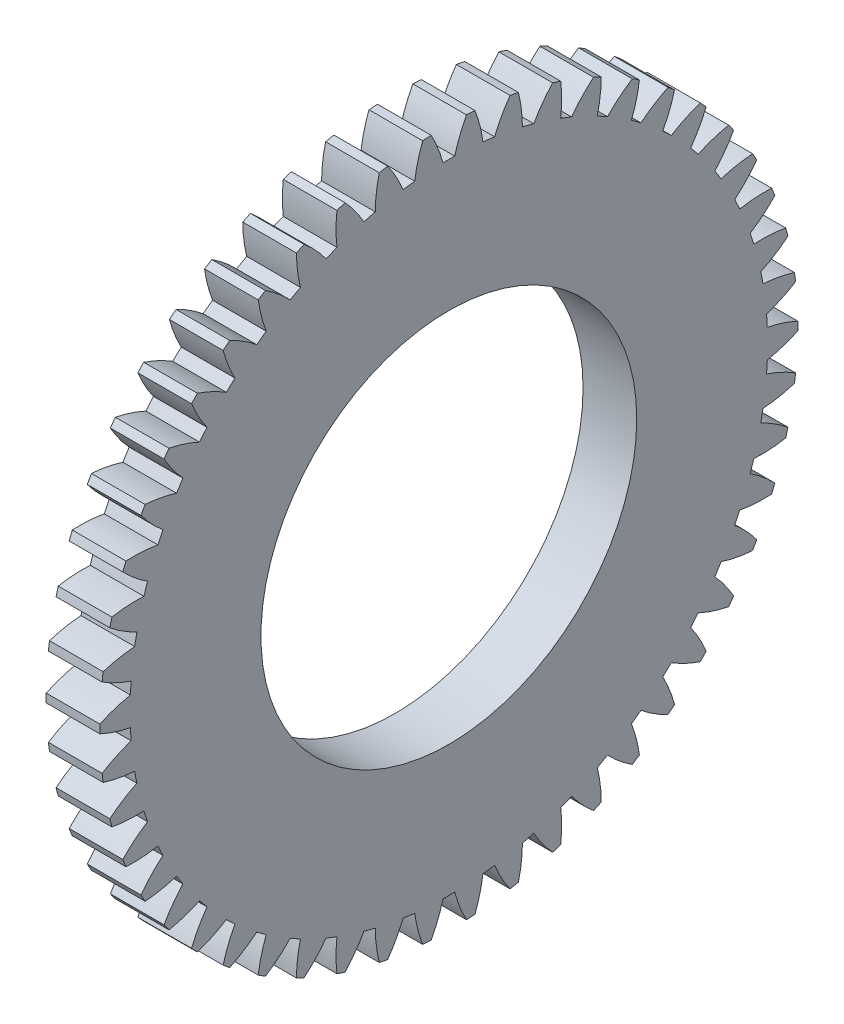
SolidWorks part; units mm, degrees
ref_plane "Front Plane" through (0, 0, 0) normal (0, 0, 1) x (1, 0, 0)
ref_plane "Top Plane" through (0, 0, 0) normal (0, 1, 0) x (1, 0, 0)
ref_plane "Right Plane" through (0, 0, 0) normal (1, 0, 0) x (0, 0, -1)
ref_plane "Plane1" through (-24.3289, 0, 0) normal (1, 0, 0) x (0, 0, -1)
sketch "Sketch1" plane through (-24.3289, 0, 0) normal (1, 0, 0) x (0, 0, -1)
  arc A0 (-24.5536, 1.2423) -> (-24.5261, 0.8057) centre (-12.6913, 1.7694) ccw
  arc A1 (-24.5261, 0.8057) -> (-25.6077, 0.2975) centre (-22.9558, -3.9413) ccw
  arc A2 (-25.6077, 0.2975) -> (-25.5679, -0.0171) centre (-12.6913, 1.7694) ccw
  arc A3 (-25.5679, -0.0171) -> (-24.3939, -0.2403) centre (-24.0535, 4.7481) ccw
  arc A4 (-24.3939, -0.2403) -> (-24.312, -0.67) centre (-12.6913, 1.7694) ccw
  arc A5 (-24.312, -0.67) -> (-25.3213, -1.3097) centre (-22.1591, -5.1827) ccw
  arc A6 (-25.3213, -1.3097) -> (-25.2425, -1.6168) centre (-12.6913, 1.7694) ccw
  arc A7 (-25.2425, -1.6168) -> (-24.0498, -1.6912) centre (-24.3372, 3.3005) ccw
  arc A8 (-24.0498, -1.6912) -> (-23.9146, -2.1072) centre (-12.6913, 1.7694) ccw
  arc A9 (-23.9146, -2.1072) -> (-24.8358, -2.8684) centre (-21.2131, -6.3145) ccw
  arc A10 (-24.8358, -2.8684) -> (-24.7191, -3.1632) centre (-12.6913, 1.7694) ccw
  arc A11 (-24.7191, -3.1632) -> (-23.5265, -3.0875) centre (-24.4373, 1.8288) ccw
  arc A12 (-23.5265, -3.0875) -> (-23.3402, -3.4833) centre (-12.6913, 1.7694) ccw
  arc A13 (-23.3402, -3.4833) -> (-24.1588, -4.354) centre (-20.1327, -7.3189) ccw
  arc A14 (-24.1588, -4.354) -> (-24.006, -4.6318) centre (-12.6913, 1.7694) ccw
  arc A15 (-24.006, -4.6318) -> (-22.8323, -4.4072) centre (-24.3521, 0.3562) ccw
  arc A16 (-22.8323, -4.4072) -> (-22.5979, -4.7765) centre (-12.6913, 1.7694) ccw
  arc A17 (-22.5979, -4.7765) -> (-23.3009, -5.7429) centre (-18.935, -8.1799) ccw
  arc A18 (-23.3009, -5.7429) -> (-23.1145, -5.9995) centre (-12.6913, 1.7694) ccw
  arc A19 (-23.1145, -5.9995) -> (-21.9782, -5.6295) centre (-24.083, -1.0942) ccw
  arc A20 (-21.9782, -5.6295) -> (-21.6994, -5.9666) centre (-12.6913, 1.7694) ccw
  arc A21 (-21.6994, -5.9666) -> (-22.2757, -7.0134) centre (-17.6387, -8.884) ccw
  arc A22 (-22.2757, -7.0134) -> (-22.0586, -7.2446) centre (-12.6913, 1.7694) ccw
  arc A23 (-22.0586, -7.2446) -> (-20.9776, -6.7352) centre (-23.6343, -2.4993) ccw
  arc A24 (-20.9776, -6.7352) -> (-20.6588, -7.0346) centre (-12.6913, 1.7694) ccw
  arc A25 (-20.6588, -7.0346) -> (-21.0993, -8.1454) centre (-16.2645, -9.42) ccw
  arc A26 (-21.0993, -8.1454) -> (-20.855, -8.3475) centre (-12.6913, 1.7694) ccw
  arc A27 (-20.855, -8.3475) -> (-19.8464, -7.7067) centre (-23.013, -3.8372) ccw
  arc A28 (-19.8464, -7.7067) -> (-19.4925, -7.9637) centre (-12.6913, 1.7694) ccw
  arc A29 (-19.4925, -7.9637) -> (-19.7904, -9.1211) centre (-14.8339, -9.7796) ccw
  arc A30 (-19.7904, -9.1211) -> (-19.5226, -9.291) centre (-12.6913, 1.7694) ccw
  arc A31 (-19.5226, -9.291) -> (-18.6023, -8.5287) centre (-22.2289, -5.0866) ccw
  arc A32 (-18.6023, -8.5287) -> (-18.219, -8.7394) centre (-12.6913, 1.7694) ccw
  arc A33 (-18.219, -8.7394) -> (-18.3694, -9.9249) centre (-13.3695, -9.9571) ccw
  arc A34 (-18.3694, -9.9249) -> (-18.0825, -10.0599) centre (-12.6913, 1.7694) ccw
  arc A35 (-18.0825, -10.0599) -> (-17.265, -9.1883) centre (-21.2944, -6.228) ccw
  arc A36 (-17.265, -9.1883) -> (-16.8583, -9.3494) centre (-12.6913, 1.7694) ccw
  arc A37 (-16.8583, -9.3494) -> (-16.859, -10.5444) centre (-11.8945, -9.9497) ccw
  arc A38 (-16.859, -10.5444) -> (-16.5574, -10.6424) centre (-12.6913, 1.7694) ccw
  arc A39 (-16.5574, -10.6424) -> (-15.8555, -9.6752) centre (-20.2242, -7.2432) ccw
  arc A40 (-15.8555, -9.6752) -> (-15.4319, -9.784) centre (-12.6913, 1.7694) ccw
  arc A41 (-15.4319, -9.784) -> (-15.2828, -10.9696) centre (-10.4319, -9.7574) ccw
  arc A42 (-15.2828, -10.9696) -> (-14.9713, -11.0291) centre (-12.6913, 1.7694) ccw
  arc A43 (-14.9713, -11.0291) -> (-14.3962, -9.9815) centre (-19.0352, -8.1162) ccw
  arc A44 (-14.3962, -9.9815) -> (-13.9622, -10.0363) centre (-12.6913, 1.7694) ccw
  arc A45 (-13.9622, -10.0363) -> (-13.6657, -11.194) centre (-9.0051, -9.3833) ccw
  arc A46 (-13.6657, -11.194) -> (-13.3493, -11.2139) centre (-12.6913, 1.7694) ccw
  arc A47 (-13.3493, -11.2139) -> (-12.91, -10.1025) centre (-17.7462, -8.8334) ccw
  arc A48 (-12.91, -10.1025) -> (-12.4726, -10.1025) centre (-12.6913, 1.7694) ccw
  arc A49 (-12.4726, -10.1025) -> (-12.0333, -11.2139) centre (-7.6363, -8.8334) ccw
  arc A50 (-12.0333, -11.2139) -> (-11.7168, -11.194) centre (-12.6913, 1.7694) ccw
  arc A51 (-11.7168, -11.194) -> (-11.4203, -10.0363) centre (-16.3775, -9.3833) ccw
  arc A52 (-11.4203, -10.0363) -> (-10.9863, -9.9815) centre (-12.6913, 1.7694) ccw
  arc A53 (-10.9863, -9.9815) -> (-10.4112, -11.0291) centre (-6.3473, -8.1162) ccw
  arc A54 (-10.4112, -11.0291) -> (-10.0998, -10.9696) centre (-12.6913, 1.7694) ccw
  arc A55 (-10.0998, -10.9696) -> (-9.9507, -9.784) centre (-14.9506, -9.7574) ccw
  arc A56 (-9.9507, -9.784) -> (-9.527, -9.6752) centre (-12.6913, 1.7694) ccw
  arc A57 (-9.527, -9.6752) -> (-8.8251, -10.6424) centre (-5.1583, -7.2432) ccw
  arc A58 (-8.8251, -10.6424) -> (-8.5236, -10.5444) centre (-12.6913, 1.7694) ccw
  arc A59 (-8.5236, -10.5444) -> (-8.5242, -9.3494) centre (-13.4881, -9.9497) ccw
  arc A60 (-8.5242, -9.3494) -> (-8.1176, -9.1883) centre (-12.6913, 1.7694) ccw
  arc A61 (-8.1176, -9.1883) -> (-7.3, -10.0599) centre (-4.0881, -6.228) ccw
  arc A62 (-7.3, -10.0599) -> (-7.0131, -9.9249) centre (-12.6913, 1.7694) ccw
  arc A63 (-7.0131, -9.9249) -> (-7.1635, -8.7394) centre (-12.013, -9.9571) ccw
  arc A64 (-7.1635, -8.7394) -> (-6.7802, -8.5287) centre (-12.6913, 1.7694) ccw
  arc A65 (-6.7802, -8.5287) -> (-5.8599, -9.291) centre (-3.1536, -5.0866) ccw
  arc A66 (-5.8599, -9.291) -> (-5.5922, -9.1211) centre (-12.6913, 1.7694) ccw
  arc A67 (-5.5922, -9.1211) -> (-5.89, -7.9637) centre (-10.5486, -9.7796) ccw
  arc A68 (-5.89, -7.9637) -> (-5.5362, -7.7067) centre (-12.6913, 1.7694) ccw
  arc A69 (-5.5362, -7.7067) -> (-4.5275, -8.3475) centre (-2.3696, -3.8372) ccw
  arc A70 (-4.5275, -8.3475) -> (-4.2832, -8.1454) centre (-12.6913, 1.7694) ccw
  arc A71 (-4.2832, -8.1454) -> (-4.7238, -7.0346) centre (-9.118, -9.42) ccw
  arc A72 (-4.7238, -7.0346) -> (-4.4049, -6.7352) centre (-12.6913, 1.7694) ccw
  arc A73 (-4.4049, -6.7352) -> (-3.3239, -7.2446) centre (-1.7482, -2.4993) ccw
  arc A74 (-3.3239, -7.2446) -> (-3.1069, -7.0134) centre (-12.6913, 1.7694) ccw
  arc A75 (-3.1069, -7.0134) -> (-3.6831, -5.9666) centre (-7.7438, -8.884) ccw
  arc A76 (-3.6831, -5.9666) -> (-3.4043, -5.6295) centre (-12.6913, 1.7694) ccw
  arc A77 (-3.4043, -5.6295) -> (-2.268, -5.9995) centre (-1.2995, -1.0942) ccw
  arc A78 (-2.268, -5.9995) -> (-2.0816, -5.7429) centre (-12.6913, 1.7694) ccw
  arc A79 (-2.0816, -5.7429) -> (-2.7846, -4.7765) centre (-6.4476, -8.1799) ccw
  arc A80 (-2.7846, -4.7765) -> (-2.5502, -4.4072) centre (-12.6913, 1.7694) ccw
  arc A81 (-2.5502, -4.4072) -> (-1.3765, -4.6318) centre (-1.0304, 0.3562) ccw
  arc A82 (-1.3765, -4.6318) -> (-1.2238, -4.354) centre (-12.6913, 1.7694) ccw
  arc A83 (-1.2238, -4.354) -> (-2.0423, -3.4833) centre (-5.2498, -7.3189) ccw
  arc A84 (-2.0423, -3.4833) -> (-1.8561, -3.0875) centre (-12.6913, 1.7694) ccw
  arc A85 (-1.8561, -3.0875) -> (-0.6634, -3.1632) centre (-0.9453, 1.8288) ccw
  arc A86 (-0.6634, -3.1632) -> (-0.5467, -2.8684) centre (-12.6913, 1.7694) ccw
  arc A87 (-0.5467, -2.8684) -> (-1.4679, -2.1072) centre (-4.1694, -6.3145) ccw
  arc A88 (-1.4679, -2.1072) -> (-1.3328, -1.6912) centre (-12.6913, 1.7694) ccw
  arc A89 (-1.3328, -1.6912) -> (-0.14, -1.6168) centre (-1.0453, 3.3005) ccw
  arc A90 (-0.14, -1.6168) -> (-0.0612, -1.3097) centre (-12.6913, 1.7694) ccw
  arc A91 (-0.0612, -1.3097) -> (-1.0705, -0.67) centre (-3.2235, -5.1827) ccw
  arc A92 (-1.0705, -0.67) -> (-0.9886, -0.2403) centre (-12.6913, 1.7694) ccw
  arc A93 (-0.9886, -0.2403) -> (0.1854, -0.0171) centre (-1.329, 4.7481) ccw
  arc A94 (0.1854, -0.0171) -> (0.2251, 0.2975) centre (-12.6913, 1.7694) ccw
  arc A95 (0.2251, 0.2975) -> (-0.8564, 0.8057) centre (-2.4268, -3.9413) ccw
  arc A96 (-0.8564, 0.8057) -> (-0.829, 1.2423) centre (-12.6913, 1.7694) ccw
  arc A97 (-0.829, 1.2423) -> (0.3078, 1.6109) centre (-1.792, 6.1486) ccw
  arc A98 (0.3078, 1.6109) -> (0.3078, 1.928) centre (-12.6913, 1.7694) ccw
  arc A99 (0.3078, 1.928) -> (-0.829, 2.2966) centre (-1.792, -2.6098) ccw
  arc A100 (-0.829, 2.2966) -> (-0.8564, 2.7332) centre (-12.6913, 1.7694) ccw
  arc A101 (-0.8564, 2.7332) -> (0.2251, 3.2414) centre (-2.4268, 7.4802) ccw
  arc A102 (0.2251, 3.2414) -> (0.1854, 3.5559) centre (-12.6913, 1.7694) ccw
  arc A103 (0.1854, 3.5559) -> (-0.9886, 3.7792) centre (-1.329, -1.2092) ccw
  arc A104 (-0.9886, 3.7792) -> (-1.0705, 4.2089) centre (-12.6913, 1.7694) ccw
  arc A105 (-1.0705, 4.2089) -> (-0.0612, 4.8486) centre (-3.2235, 8.7216) ccw
  arc A106 (-0.0612, 4.8486) -> (-0.14, 5.1557) centre (-12.6913, 1.7694) ccw
  arc A107 (-0.14, 5.1557) -> (-1.3328, 5.2301) centre (-1.0453, 0.2384) ccw
  arc A108 (-1.3328, 5.2301) -> (-1.4679, 5.6461) centre (-12.6913, 1.7694) ccw
  arc A109 (-1.4679, 5.6461) -> (-0.5467, 6.4073) centre (-4.1694, 9.8534) ccw
  arc A110 (-0.5467, 6.4073) -> (-0.6634, 6.7021) centre (-12.6913, 1.7694) ccw
  arc A111 (-0.6634, 6.7021) -> (-1.8561, 6.6264) centre (-0.9453, 1.7101) ccw
  arc A112 (-1.8561, 6.6264) -> (-2.0423, 7.0222) centre (-12.6913, 1.7694) ccw
  arc A113 (-2.0423, 7.0222) -> (-1.2238, 7.8928) centre (-5.2498, 10.8577) ccw
  arc A114 (-1.2238, 7.8928) -> (-1.3765, 8.1707) centre (-12.6913, 1.7694) ccw
  arc A115 (-1.3765, 8.1707) -> (-2.5502, 7.9461) centre (-1.0304, 3.1827) ccw
  arc A116 (-2.5502, 7.9461) -> (-2.7846, 8.3154) centre (-12.6913, 1.7694) ccw
  arc A117 (-2.7846, 8.3154) -> (-2.0816, 9.2818) centre (-6.4476, 11.7187) ccw
  arc A118 (-2.0816, 9.2818) -> (-2.268, 9.5383) centre (-12.6913, 1.7694) ccw
  arc A119 (-2.268, 9.5383) -> (-3.4043, 9.1684) centre (-1.2995, 4.633) ccw
  arc A120 (-3.4043, 9.1684) -> (-3.6831, 9.5054) centre (-12.6913, 1.7694) ccw
  arc A121 (-3.6831, 9.5054) -> (-3.1069, 10.5523) centre (-7.7438, 12.4228) ccw
  arc A122 (-3.1069, 10.5523) -> (-3.3239, 10.7835) centre (-12.6913, 1.7694) ccw
  arc A123 (-3.3239, 10.7835) -> (-4.4049, 10.274) centre (-1.7482, 6.0382) ccw
  arc A124 (-4.4049, 10.274) -> (-4.7238, 10.5735) centre (-12.6913, 1.7694) ccw
  arc A125 (-4.7238, 10.5735) -> (-4.2832, 11.6843) centre (-9.118, 12.9589) ccw
  arc A126 (-4.2832, 11.6843) -> (-4.5275, 11.8864) centre (-12.6913, 1.7694) ccw
  arc A127 (-4.5275, 11.8864) -> (-5.5362, 11.2455) centre (-2.3696, 7.3761) ccw
  arc A128 (-5.5362, 11.2455) -> (-5.89, 11.5026) centre (-12.6913, 1.7694) ccw
  arc A129 (-5.89, 11.5026) -> (-5.5922, 12.6599) centre (-10.5486, 13.3185) ccw
  arc A130 (-5.5922, 12.6599) -> (-5.8599, 12.8298) centre (-12.6913, 1.7694) ccw
  arc A131 (-5.8599, 12.8298) -> (-6.7802, 12.0676) centre (-3.1536, 8.6255) ccw
  arc A132 (-6.7802, 12.0676) -> (-7.1635, 12.2783) centre (-12.6913, 1.7694) ccw
  arc A133 (-7.1635, 12.2783) -> (-7.0131, 13.4638) centre (-12.013, 13.496) ccw
  arc A134 (-7.0131, 13.4638) -> (-7.3, 13.5988) centre (-12.6913, 1.7694) ccw
  arc A135 (-7.3, 13.5988) -> (-8.1176, 12.7272) centre (-4.0881, 9.7668) ccw
  arc A136 (-8.1176, 12.7272) -> (-8.5242, 12.8882) centre (-12.6913, 1.7694) ccw
  arc A137 (-8.5242, 12.8882) -> (-8.5236, 14.0833) centre (-13.4881, 13.4885) ccw
  arc A138 (-8.5236, 14.0833) -> (-8.8251, 14.1812) centre (-12.6913, 1.7694) ccw
  arc A139 (-8.8251, 14.1812) -> (-9.527, 13.2141) centre (-5.1583, 10.782) ccw
  arc A140 (-9.527, 13.2141) -> (-9.9507, 13.3228) centre (-12.6913, 1.7694) ccw
  arc A141 (-9.9507, 13.3228) -> (-10.0998, 14.5085) centre (-14.9506, 13.2963) ccw
  arc A142 (-10.0998, 14.5085) -> (-10.4112, 14.5679) centre (-12.6913, 1.7694) ccw
  arc A143 (-10.4112, 14.5679) -> (-10.9863, 13.5204) centre (-6.3473, 11.6551) ccw
  arc A144 (-10.9863, 13.5204) -> (-11.4203, 13.5752) centre (-12.6913, 1.7694) ccw
  arc A145 (-11.4203, 13.5752) -> (-11.7168, 14.7329) centre (-16.3775, 12.9222) ccw
  arc A146 (-11.7168, 14.7329) -> (-12.0333, 14.7528) centre (-12.6913, 1.7694) ccw
  arc A147 (-12.0333, 14.7528) -> (-12.4726, 13.6414) centre (-7.6363, 12.3723) ccw
  arc A148 (-12.4726, 13.6414) -> (-12.91, 13.6414) centre (-12.6913, 1.7694) ccw
  arc A149 (-12.91, 13.6414) -> (-13.3493, 14.7528) centre (-17.7462, 12.3723) ccw
  arc A150 (-13.3493, 14.7528) -> (-13.6657, 14.7329) centre (-12.6913, 1.7694) ccw
  arc A151 (-13.6657, 14.7329) -> (-13.9622, 13.5752) centre (-9.0051, 12.9222) ccw
  arc A152 (-13.9622, 13.5752) -> (-14.3962, 13.5204) centre (-12.6913, 1.7694) ccw
  arc A153 (-14.3962, 13.5204) -> (-14.9713, 14.5679) centre (-19.0352, 11.6551) ccw
  arc A154 (-14.9713, 14.5679) -> (-15.2828, 14.5085) centre (-12.6913, 1.7694) ccw
  arc A155 (-15.2828, 14.5085) -> (-15.4319, 13.3228) centre (-10.4319, 13.2963) ccw
  arc A156 (-15.4319, 13.3228) -> (-15.8555, 13.2141) centre (-12.6913, 1.7694) ccw
  arc A157 (-15.8555, 13.2141) -> (-16.5574, 14.1812) centre (-20.2242, 10.782) ccw
  arc A158 (-16.5574, 14.1812) -> (-16.859, 14.0833) centre (-12.6913, 1.7694) ccw
  arc A159 (-16.859, 14.0833) -> (-16.8583, 12.8882) centre (-11.8945, 13.4885) ccw
  arc A160 (-16.8583, 12.8882) -> (-17.265, 12.7272) centre (-12.6913, 1.7694) ccw
  arc A161 (-17.265, 12.7272) -> (-18.0825, 13.5988) centre (-21.2944, 9.7668) ccw
  arc A162 (-18.0825, 13.5988) -> (-18.3694, 13.4638) centre (-12.6913, 1.7694) ccw
  arc A163 (-18.3694, 13.4638) -> (-18.219, 12.2783) centre (-13.3695, 13.496) ccw
  arc A164 (-18.219, 12.2783) -> (-18.6023, 12.0676) centre (-12.6913, 1.7694) ccw
  arc A165 (-18.6023, 12.0676) -> (-19.5226, 12.8298) centre (-22.2289, 8.6255) ccw
  arc A166 (-19.5226, 12.8298) -> (-19.7904, 12.6599) centre (-12.6913, 1.7694) ccw
  arc A167 (-19.7904, 12.6599) -> (-19.4925, 11.5026) centre (-14.8339, 13.3185) ccw
  arc A168 (-19.4925, 11.5026) -> (-19.8464, 11.2455) centre (-12.6913, 1.7694) ccw
  arc A169 (-19.8464, 11.2455) -> (-20.855, 11.8864) centre (-23.013, 7.3761) ccw
  arc A170 (-20.855, 11.8864) -> (-21.0993, 11.6843) centre (-12.6913, 1.7694) ccw
  arc A171 (-21.0993, 11.6843) -> (-20.6588, 10.5735) centre (-16.2645, 12.9589) ccw
  arc A172 (-20.6588, 10.5735) -> (-20.9776, 10.274) centre (-12.6913, 1.7694) ccw
  arc A173 (-20.9776, 10.274) -> (-22.0586, 10.7835) centre (-23.6343, 6.0382) ccw
  arc A174 (-22.0586, 10.7835) -> (-22.2757, 10.5523) centre (-12.6913, 1.7694) ccw
  arc A175 (-22.2757, 10.5523) -> (-21.6994, 9.5054) centre (-17.6387, 12.4228) ccw
  arc A176 (-21.6994, 9.5054) -> (-21.9782, 9.1684) centre (-12.6913, 1.7694) ccw
  arc A177 (-21.9782, 9.1684) -> (-23.1145, 9.5383) centre (-24.083, 4.633) ccw
  arc A178 (-23.1145, 9.5383) -> (-23.3009, 9.2818) centre (-12.6913, 1.7694) ccw
  arc A179 (-23.3009, 9.2818) -> (-22.5979, 8.3154) centre (-18.935, 11.7187) ccw
  arc A180 (-22.5979, 8.3154) -> (-22.8323, 7.9461) centre (-12.6913, 1.7694) ccw
  arc A181 (-22.8323, 7.9461) -> (-24.006, 8.1707) centre (-24.3521, 3.1827) ccw
  arc A182 (-24.006, 8.1707) -> (-24.1588, 7.8928) centre (-12.6913, 1.7694) ccw
  arc A183 (-24.1588, 7.8928) -> (-23.3402, 7.0222) centre (-20.1327, 10.8577) ccw
  arc A184 (-23.3402, 7.0222) -> (-23.5265, 6.6264) centre (-12.6913, 1.7694) ccw
  arc A185 (-23.5265, 6.6264) -> (-24.7191, 6.7021) centre (-24.4373, 1.7101) ccw
  arc A186 (-24.7191, 6.7021) -> (-24.8358, 6.4073) centre (-12.6913, 1.7694) ccw
  arc A187 (-24.8358, 6.4073) -> (-23.9146, 5.6461) centre (-21.2131, 9.8534) ccw
  arc A188 (-23.9146, 5.6461) -> (-24.0498, 5.2301) centre (-12.6913, 1.7694) ccw
  arc A189 (-24.0498, 5.2301) -> (-25.2425, 5.1557) centre (-24.3372, 0.2384) ccw
  arc A190 (-25.2425, 5.1557) -> (-25.3213, 4.8486) centre (-12.6913, 1.7694) ccw
  arc A191 (-25.3213, 4.8486) -> (-24.312, 4.2089) centre (-22.1591, 8.7216) ccw
  arc A192 (-24.312, 4.2089) -> (-24.3939, 3.7792) centre (-12.6913, 1.7694) ccw
  arc A193 (-24.3939, 3.7792) -> (-25.5679, 3.5559) centre (-24.0535, -1.2092) ccw
  arc A194 (-25.5679, 3.5559) -> (-25.6077, 3.2414) centre (-12.6913, 1.7694) ccw
  arc A195 (-25.6077, 3.2414) -> (-24.5261, 2.7332) centre (-22.9558, 7.4802) ccw
  arc A196 (-24.5261, 2.7332) -> (-24.5536, 2.2966) centre (-12.6913, 1.7694) ccw
  arc A197 (-24.5536, 2.2966) -> (-25.6903, 1.928) centre (-23.5906, -2.6098) ccw
  arc A198 (-25.6903, 1.928) -> (-25.6903, 1.6109) centre (-12.6913, 1.7694) ccw
  arc A199 (-25.6903, 1.6109) -> (-24.5536, 1.2423) centre (-23.5906, 6.1486) ccw
  circle A200 centre (-12.6913, 1.7694) radius 7.75
  dimension "D1" = 15.5
extrude "Boss-Extrude1" add sketch "Sketch1" against normal blind 2
sketch "Sketch2" plane through (-24.3289, 0, 0) normal (1, 0, 0) x (0, 0, -1)
  circle A0 centre (-12.6913, 1.7694) radius 7.75 construction
  circle A1 centre (-12.6913, 1.7694) radius 7.75
  circle A2 centre (-12.6913, 1.7694) radius 7
  dimension "D1" = 14
extrude "Boss-Extrude2" add sketch "Sketch2" against normal up to surface (2 mm away) up to face at (-26.3289, 1.7694, 20.4413)
